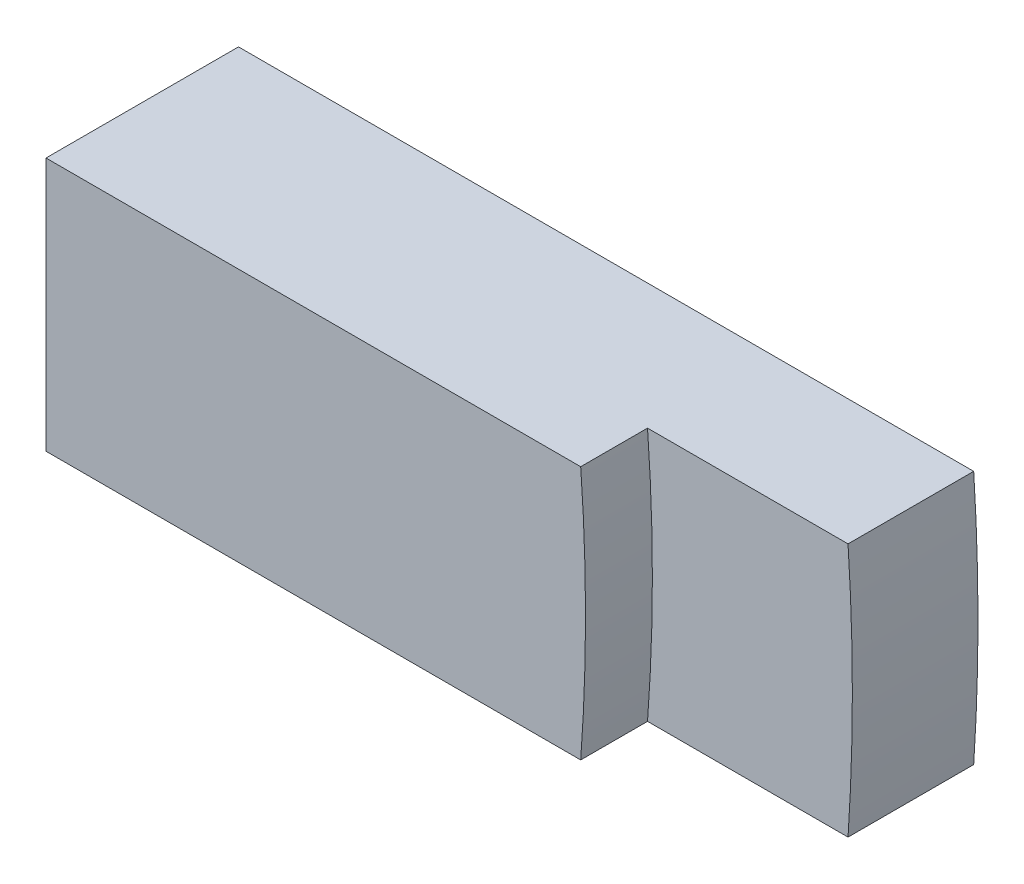
SolidWorks part; units mm, degrees
ref_plane "Front Plane" through (0, 0, 0) normal (0, 0, 1) x (1, 0, 0)
ref_plane "Top Plane" through (0, 0, 0) normal (0, 1, 0) x (1, 0, 0)
ref_plane "Right Plane" through (0, 0, 0) normal (1, 0, 0) x (0, 0, -1)
sketch "Sketch2" plane through (0, 0, 0) normal (0, 0, 1) x (1, 0, 0)
  line L1 (-2.54, -1.2065) -> (2.54, -1.2065)
  line L2 (-2.54, -1.2065) -> (-2.54, 1.2065)
  line L3 (-2.54, 1.2065) -> (2.54, 1.2065)
  line L5 (-2.54, -1.2065) -> (2.54, 1.2065) construction
  line L6 (-2.54, 1.2065) -> (2.54, -1.2065) construction
  arc A0 (2.54, -1.2065) -> (2.54, 1.2065) centre (-13.2891, 0) ccw
  point P0 (0, 0)
  dimension "D1" = 15.875
  dimension "D2" = 2.413
  dimension "D3" = 5.08
extrude "Boss-Extrude1" add sketch "Sketch2" along normal blind 1.8288
sketch "Sketch3" plane through (0, 0, 0) normal (0, 0, 1) x (1, 0, 0)
  line L1 (2.54, 1.2065) -> (4.445, 1.2065)
  line L2 (2.54, 1.2065) -> (2.54, -1.2065)
  line L3 (2.54, -1.2065) -> (4.445, -1.2065)
  arc A0 (4.445, 1.2065) -> (4.445, -1.2065) centre (-13.294, 0) cw
  dimension "D2" = 17.78
  dimension "D1" = 2.413
  dimension "D3" = 1.905
extrude "Boss-Extrude2" add sketch "Sketch3" along normal blind 1.1938
